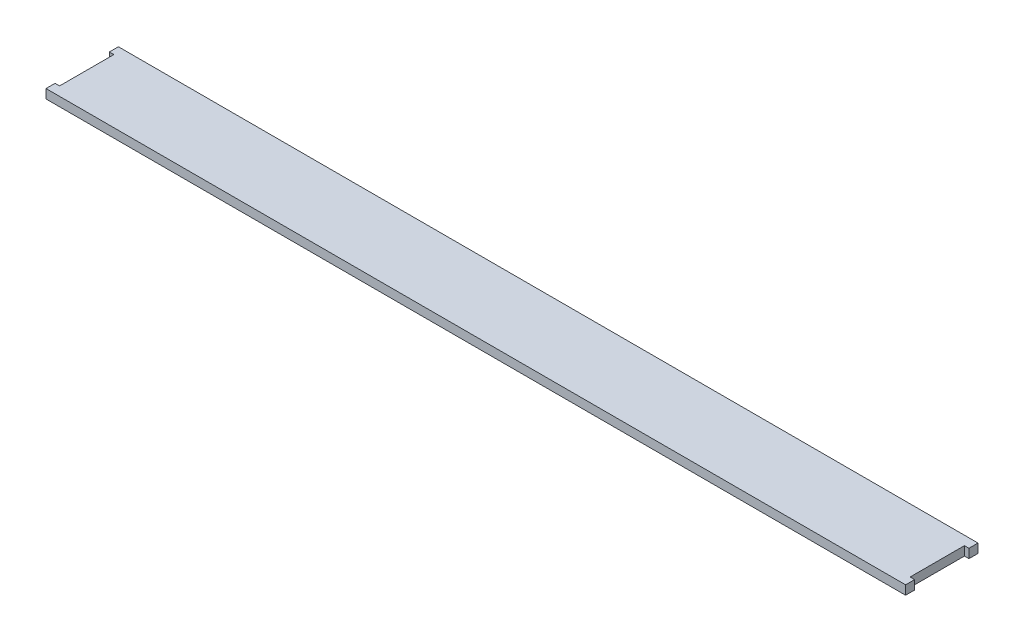
SolidWorks part; units mm, degrees
ref_plane "Front Plane" through (0, 0, 0) normal (0, 0, 1) x (1, 0, 0)
ref_plane "Top Plane" through (0, 0, 0) normal (0, 1, 0) x (1, 0, 0)
ref_plane "Right Plane" through (0, 0, 0) normal (1, 0, 0) x (0, 0, -1)
sketch "Sketch1" plane through (0, 0, 0) normal (0, 1, 0) x (1, 0, 0)
  line L0 (-298.45, 21.8115) -> (-298.45, -16.2885)
  line L1 (301.625, 28.1615) -> (-301.625, 28.1615)
  line L2 (301.625, 28.1615) -> (301.625, 21.8115)
  line L3 (301.625, -22.6385) -> (-301.625, -22.6385)
  line L4 (-301.625, 28.1615) -> (-301.625, 21.8115)
  line L5 (-301.625, 21.8115) -> (-298.45, 21.8115)
  line L6 (-301.625, -16.2885) -> (-298.45, -16.2885)
  line L7 (-301.625, -16.2885) -> (-301.625, -22.6385)
  line L8 (-298.45, 2.7615) -> (-286.7076, 2.7615) construction
  line L9 (301.625, -16.2885) -> (301.625, -22.6385)
  line L10 (301.625, -16.2885) -> (298.45, -16.2885)
  line L11 (301.625, 21.8115) -> (298.45, 21.8115)
  line L13 (298.45, 21.8115) -> (298.45, -16.2885)
  line L21 (0, -22.6385) -> (0, -9.7718) construction
  line L22 (298.45, 2.7615) -> (286.7076, 2.7615) construction
  dimension "D1" = 603.25
  dimension "D2" = 301.625
  dimension "D3" = 50.8
  dimension "D4" = 3.175
  dimension "D5" = 6.35
  dimension "D6" = 6.35
  dimension "D7" = 0
  dimension "D8" = 3.175
  dimension "D9" = 6.35
  dimension "D10" = 6.35
extrude "Boss-Extrude1" add sketch "Sketch1" along normal blind 6.35
equation "\"D2@Sketch1\" = \"D1@Sketch1\"/2"
